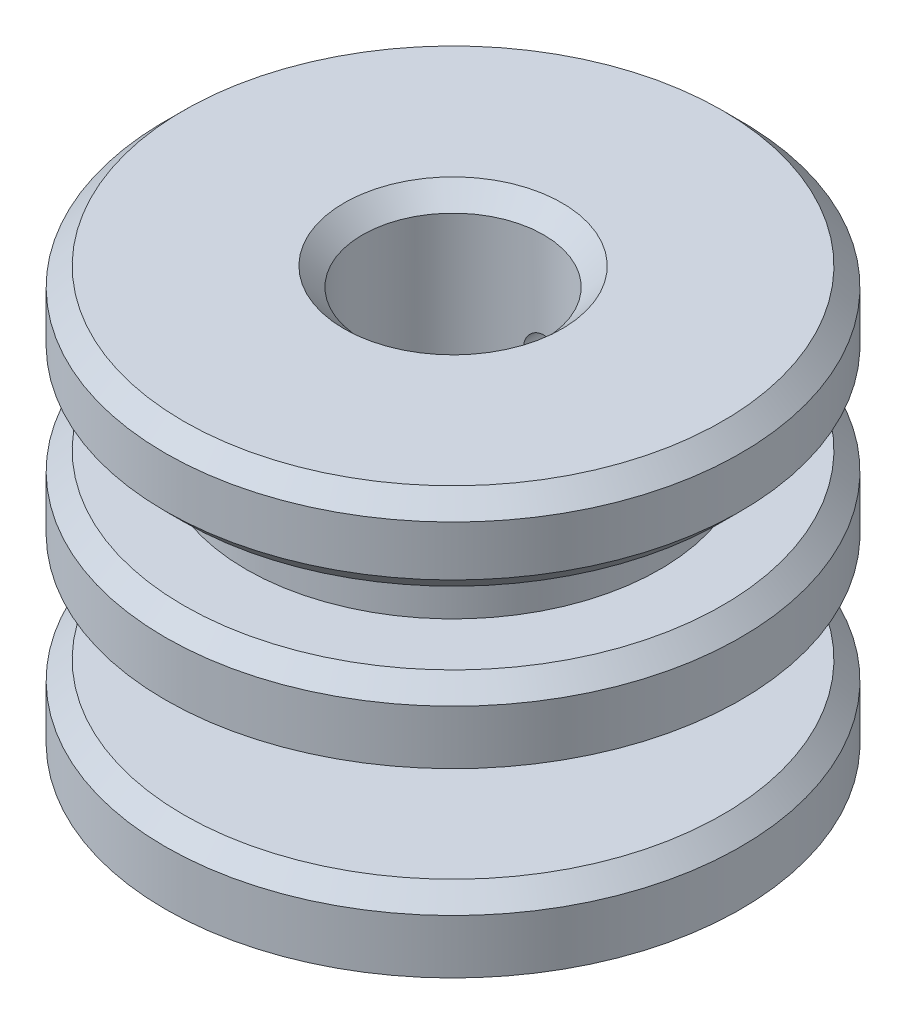
SolidWorks part; units mm, degrees
ref_plane "Front Plane" through (0, 0, 0) normal (0, 0, 1) x (1, 0, 0)
ref_plane "Top Plane" through (0, 0, 0) normal (0, 1, 0) x (1, 0, 0)
ref_plane "Right Plane" through (0, 0, 0) normal (1, 0, 0) x (0, 0, -1)
sketch "Sketch1" plane through (0, 0, 0) normal (0, 1, 0) x (1, 0, 0)
  circle A0 centre (0, 0) radius 2.3813
  circle A1 centre (0, 0) radius 7.9375
  dimension "D1" = 4.7625
  dimension "D2" = 15.875
extrude "Boss-Extrude1" add sketch "Sketch1" along normal blind 2
sketch "Sketch2" plane through (0, 2, 0) normal (0, 1, 0) x (1, 0, 0)
  circle A0 centre (0, 0) radius 1.1375
  circle A1 centre (0, 0) radius 3.3707
  dimension "D1" = 2.275
  dimension "D2" = 6.7415
extrude "Boss-Extrude2" add sketch "Sketch2" along normal blind 1.5
sketch "Sketch3" plane through (0, 3.5, 0) normal (0, 1, 0) x (1, 0, 0)
  circle A0 centre (0, 0) radius 3.3707
  circle A1 centre (0, 0) radius 2.5
  circle A2 centre (0, 0) radius 3.3707 construction
  dimension "D1" = 5
extrude "Boss-Extrude3" add sketch "Sketch3" along normal blind 1.5
sketch "Sketch5" plane through (0, 5, 0) normal (0, 1, 0) x (1, 0, 0)
  circle A0 centre (0, 0) radius 2.5
  circle A1 centre (0, 0) radius 7.9375
  circle A2 centre (0, 0) radius 7.9375 construction
  circle A3 centre (0, 0) radius 2.5 construction
extrude "Boss-Extrude4" add sketch "Sketch5" along normal blind 2
sketch "Sketch6" plane through (0, 7, 0) normal (0, 1, 0) x (1, 0, 0)
  circle A0 centre (0, 0) radius 2.5
  circle A1 centre (0, 0) radius 5.706
  circle A2 centre (0, 0) radius 2.5 construction
  dimension "D1" = 11.4121
extrude "Boss-Extrude5" add sketch "Sketch6" along normal blind 2
sketch "Sketch7" plane through (0, 9, 0) normal (0, 1, 0) x (1, 0, 0)
  circle A0 centre (0, 0) radius 2.5
  circle A1 centre (0, 0) radius 7.9375
  circle A2 centre (0, 0) radius 7.9375 construction
  circle A3 centre (0, 0) radius 2.5 construction
extrude "Boss-Extrude6" add sketch "Sketch7" along normal blind 2.4
sketch "Sketch8" plane through (0, 0, 0) normal (0, 0, 1) x (1, 0, 0)
  line L0 (0, 0) -> (0, 2) construction
  line L1 (0, 2) -> (0, 5) construction
  line L2 (0, 5) -> (0, 7) construction
  line L3 (0, 7) -> (0, 9) construction
  line L4 (3.3707, 2) -> (-3.3707, 2) construction
  line L5 (-3.3707, 5) -> (3.3707, 5) construction
  line L6 (5.706, 7) -> (-5.706, 7) construction
  line L7 (-5.706, 9) -> (5.706, 9) construction
  circle A0 centre (0, 8) radius 0.5
  circle A1 centre (0, 4) radius 0.5
  dimension "D1" = 1
  dimension "D2" = 1
  dimension "D4" = 2
  dimension "D3" = 1
extrude "Cut-Extrude1" cut sketch "Sketch8" against normal through all
chamfer "Chamfer1" distance 0.508 angle 45 5 edges at (0, 11.4, 7.9375) (0, 11.4, 2.5) (0, 2, 7.9375) (0, 7, 7.9375) (0, 9, 7.9375)
